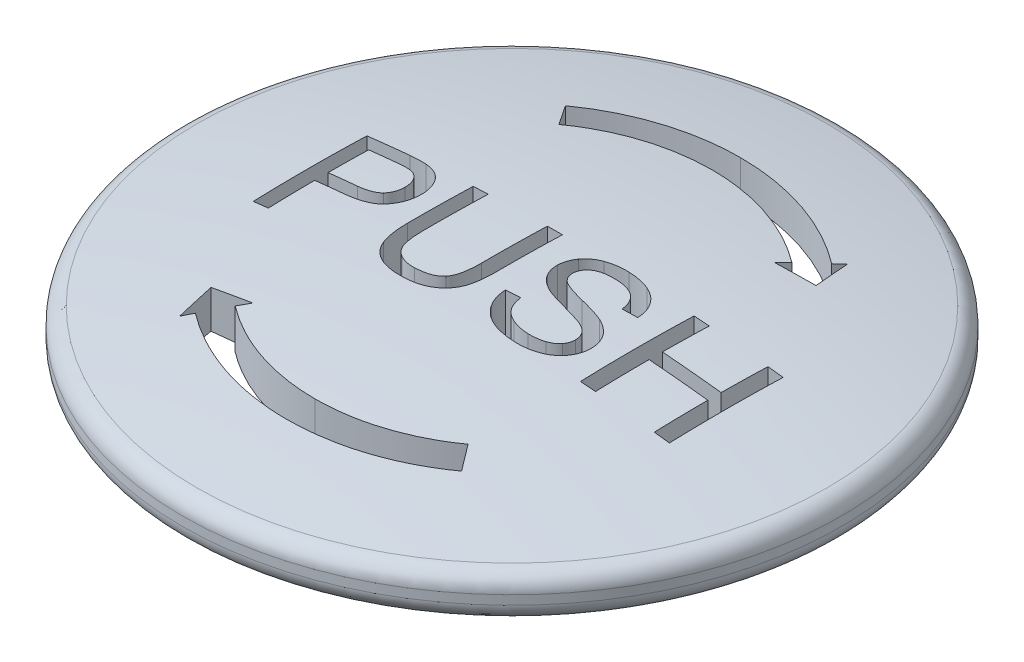
SolidWorks part; units mm, degrees
ref_plane "Front Plane" through (0, 0, 0) normal (0, 0, 1) x (1, 0, 0)
ref_plane "Top Plane" through (0, 0, 0) normal (0, 1, 0) x (1, 0, 0)
ref_plane "Right Plane" through (0, 0, 0) normal (1, 0, 0) x (0, 0, -1)
sketch "Sketch1" plane through (0, 0, 0) normal (0, 1, 0) x (1, 0, 0)
  circle A0 centre (0, 0) radius 20
  circle A1 centre (0, 0) radius 10
  dimension "D1" = 40
  dimension "D2" = 20
sketch "Sketch2" plane through (0, 0, 0) normal (0, 1, 0) x (1, 0, 0)
  circle A1 centre (0, 0) radius 10
  dimension "D1" = 20
extrude "Boss-Extrude2" add sketch "Sketch2" along normal blind 10 separate body
sketch "Sketch4" plane through (0, 0, 0) normal (0, 0, 1) x (1, 0, 0)
  line L0 (0, 10) -> (0, 15)
  line L1 (10, 10) -> (-10, 10) construction
  line L2 (0, 10) -> (21.3, 10)
  line L3 (22.5, 11.2) -> (22.5, 11.8205)
  line L4 (0, 15) -> (22.8044, 15) construction
  arc A0 (0, 15) -> (21.5211, 13) centre (0, -101.7897) cw
  arc A1 (22.5, 11.8205) -> (21.5211, 13) centre (21.3, 11.8205) ccw
  arc A2 (21.3, 10) -> (22.5, 11.2) centre (21.3, 11.2) ccw
  point P13 (22.5, 10)
  dimension "D3" = 1.2
  dimension "D1" = 5
  dimension "D2" = 22.5
  dimension "D4" = 3
revolve "Revolve1" add sketch "Sketch4" angle 360 about L0
sketch "Sketch9" plane through (0, 10, 0) normal (0, -1, 0) x (1, 0, 0)
  circle A0 centre (0, 0) radius 18
  dimension "D1" = 36
extrude "Cut-Extrude4" cut sketch "Sketch9" against normal blind 1.5
sketch "Sketch10" plane through (0, 11.5, 0) normal (0, -1, 0) x (1, 0, 0)
  circle A1 centre (0, 0) radius 18
  circle A2 centre (0, 0) radius 18
  dimension "D1" = 0
extrude "Cut-Extrude5" cut sketch "Sketch10" along normal blind 24.9
sketch "Sketch16" plane through (0, 0, 0) normal (0, 1, 0) x (1, 0, 0)
  line L0 (10.2566, 10.5007) -> (7.684, 10.2214)
  line L1 (7.684, 10.2214) -> (8.2069, 10.9019)
  line L2 (-7.9193, 11.1255) -> (-9.0492, 12.6983)
  line L3 (9.3805, 12.444) -> (9.8411, 13.0492)
  line L4 (9.8411, 13.0492) -> (10.2566, 10.5007)
  line L5 (-10.2699, -10.2796) -> (-7.6974, -10.0002)
  line L6 (-7.6974, -10.0002) -> (-8.2203, -10.6808)
  line L7 (7.9059, -10.9043) -> (9.0358, -12.4772)
  line L8 (-9.3939, -12.2228) -> (-9.8545, -12.828)
  line L9 (-9.8545, -12.828) -> (-10.2699, -10.2796)
  line L10 (-13.8958, -3.7717) -> (-13.8958, 3.9926)
  line L11 (-13.8958, 3.9926) -> (-10.9644, 3.9926)
  line L12 (-10.874, -0.6053) -> (-12.8657, -0.6053)
  line L13 (-12.8657, -0.6053) -> (-12.8657, -3.7717)
  line L14 (-12.8657, -3.7717) -> (-13.8958, -3.7717)
  line L15 (-12.8657, 0.3057) -> (-10.8596, 0.3057)
  line L16 (-10.8794, 3.0817) -> (-12.8657, 3.0817)
  line L17 (-12.8657, 3.0817) -> (-12.8657, 0.3057)
  line L18 (-1.5772, 3.9926) -> (-0.547, 3.9926)
  line L19 (-0.547, 3.9926) -> (-0.547, -0.4913)
  line L20 (-6.6413, -0.4913) -> (-6.6413, 3.9926)
  line L21 (-6.6413, 3.9926) -> (-5.6112, 3.9926)
  line L22 (-5.6112, 3.9926) -> (-5.6112, -0.4895)
  line L23 (-1.5772, -0.4895) -> (-1.5772, 3.9926)
  line L24 (0.8319, -1.2776) -> (1.7971, -1.1908)
  line L25 (6.7745, 1.802) -> (5.7877, 1.7263)
  line L26 (8.4445, -3.7717) -> (8.4445, 3.9926)
  line L27 (8.4445, 3.9926) -> (9.4746, 3.9926)
  line L28 (9.4746, 3.9926) -> (9.4746, 0.7937)
  line L29 (9.4746, 0.7937) -> (13.4868, 0.7937)
  line L30 (13.4868, 0.7937) -> (13.4868, 3.9926)
  line L31 (13.4868, 3.9926) -> (14.517, 3.9926)
  line L32 (14.517, 3.9926) -> (14.517, -3.7717)
  line L33 (14.517, -3.7717) -> (13.4868, -3.7717)
  line L34 (13.4868, -3.7717) -> (13.4868, -0.1173)
  line L35 (13.4868, -0.1173) -> (9.4746, -0.1173)
  line L36 (9.4746, -0.1173) -> (9.4746, -3.7717)
  line L37 (9.4746, -3.7717) -> (8.4445, -3.7717)
  circle A0 centre (0, 0) radius 15.6 construction
  spline S0 degree 3 poles (8.2069, 10.9019) (5.8458, 12.6991) (2.9604, 13.6721) (-0.0067, 13.6721) knots 0.2 0.2 0.2 0.2 0.3 0.3 0.3 0.3
  spline S1 degree 3 poles (-0.0067, 13.6721) (-2.8456, 13.6721) (-5.6137, 12.782) (-7.9193, 11.1255) knots 0.3 0.3 0.3 0.3 0.4 0.4 0.4 0.4
  spline S2 degree 3 poles (-9.0492, 12.6983) (-6.4141, 14.5912) (-3.2512, 15.6095) (-0.0067, 15.6095) knots 0.5 0.5 0.5 0.5 0.6 0.6 0.6 0.6
  spline S3 degree 3 poles (-0.0067, 15.6095) (3.3843, 15.6095) (6.6821, 14.4976) (9.3805, 12.444) knots 0.6 0.6 0.6 0.6 0.7 0.7 0.7 0.7
  spline S4 degree 3 poles (-8.2203, -10.6808) (-5.8592, -12.4779) (-2.9738, -13.451) (-0.0067, -13.451) knots 0.2 0.2 0.2 0.2 0.3 0.3 0.3 0.3
  spline S5 degree 3 poles (-0.0067, -13.451) (2.8323, -13.451) (5.6003, -12.5609) (7.9059, -10.9043) knots 0.3 0.3 0.3 0.3 0.4 0.4 0.4 0.4
  spline S6 degree 3 poles (9.0358, -12.4772) (6.4008, -14.3701) (3.2378, -15.3883) (-0.0067, -15.3883) knots 0.5 0.5 0.5 0.5 0.6 0.6 0.6 0.6
  spline S7 degree 3 poles (-0.0067, -15.3883) (-3.3977, -15.3883) (-6.6955, -14.2765) (-9.3939, -12.2228) knots 0.6 0.6 0.6 0.6 0.7 0.7 0.7 0.7
  spline S8 degree 3 poles (-10.9644, 3.9926) (-10.4494, 3.9926) (-10.0554, 3.9673) (-9.7825, 3.9185) knots 0.166667 0.166667 0.166667 0.166667 0.25 0.25 0.25 0.25
  spline S9 degree 3 poles (-9.7825, 3.9185) (-9.4011, 3.8553) (-9.0812, 3.7342) (-8.8227, 3.557) knots 0.25 0.25 0.25 0.25 0.333333 0.333333 0.333333 0.333333
  spline S10 degree 3 poles (-8.8227, 3.557) (-8.5642, 3.3781) (-8.3565, 3.1286) (-8.1992, 2.8088) knots 0.333333 0.333333 0.333333 0.333333 0.416667 0.416667 0.416667 0.416667
  spline S11 degree 3 poles (-8.1992, 2.8088) (-8.0419, 2.4889) (-7.9643, 2.1365) (-7.9643, 1.7515) knots 0.416667 0.416667 0.416667 0.416667 0.5 0.5 0.5 0.5
  spline S12 degree 3 poles (-7.9643, 1.7515) (-7.9643, 1.0936) (-8.1738, 0.5352) (-8.595, 0.0798) knots 0.5 0.5 0.5 0.5 0.583333 0.583333 0.583333 0.583333
  spline S13 degree 3 poles (-8.595, 0.0798) (-9.0142, -0.3776) (-9.7751, -0.6053) (-10.874, -0.6053) knots 0.583333 0.583333 0.583333 0.583333 0.666667 0.666667 0.666667 0.666667
  spline S14 degree 3 poles (-10.8596, 0.3057) (-10.1945, 0.3057) (-9.7245, 0.4286) (-9.4444, 0.6761) knots 0.111111 0.111111 0.111111 0.111111 0.222222 0.222222 0.222222 0.222222
  spline S15 degree 3 poles (-9.4444, 0.6761) (-9.1662, 0.9238) (-9.027, 1.2707) (-9.027, 1.7209) knots 0.222222 0.222222 0.222222 0.222222 0.333333 0.333333 0.333333 0.333333
  spline S16 degree 3 poles (-9.027, 1.7209) (-9.027, 2.0443) (-9.1082, 2.3226) (-9.2727, 2.5539) knots 0.333333 0.333333 0.333333 0.333333 0.444444 0.444444 0.444444 0.444444
  spline S17 degree 3 poles (-9.2727, 2.5539) (-9.4372, 2.7854) (-9.6541, 2.9389) (-9.9216, 3.0131) knots 0.444444 0.444444 0.444444 0.444444 0.555556 0.555556 0.555556 0.555556
  spline S18 degree 3 poles (-9.9216, 3.0131) (-10.0951, 3.0583) (-10.415, 3.0817) (-10.8794, 3.0817) knots 0.555556 0.555556 0.555556 0.555556 0.666667 0.666667 0.666667 0.666667
  spline S19 degree 3 poles (-0.547, -0.4913) (-0.547, -1.2722) (-0.6356, -1.8921) (-0.8109, -2.3511) knots 0.111111 0.111111 0.111111 0.111111 0.166667 0.166667 0.166667 0.166667
  spline S20 degree 3 poles (-0.8109, -2.3511) (-0.988, -2.8083) (-1.3061, -3.1825) (-1.7651, -3.4698) knots 0.166667 0.166667 0.166667 0.166667 0.222222 0.222222 0.222222 0.222222
  spline S21 degree 3 poles (-1.7651, -3.4698) (-2.2259, -3.7573) (-2.8278, -3.9018) (-3.5761, -3.9018) knots 0.222222 0.222222 0.222222 0.222222 0.277778 0.277778 0.277778 0.277778
  spline S22 degree 3 poles (-3.5761, -3.9018) (-4.3008, -3.9018) (-4.8953, -3.7771) (-5.3563, -3.5258) knots 0.277778 0.277778 0.277778 0.277778 0.333333 0.333333 0.333333 0.333333
  spline S23 degree 3 poles (-5.3563, -3.5258) (-5.8189, -3.2747) (-6.1479, -2.9132) (-6.3448, -2.4379) knots 0.333333 0.333333 0.333333 0.333333 0.388889 0.388889 0.388889 0.388889
  spline S24 degree 3 poles (-6.3448, -2.4379) (-6.5418, -1.9625) (-6.6413, -1.3138) (-6.6413, -0.4913) knots 0.388889 0.388889 0.388889 0.388889 0.444444 0.444444 0.444444 0.444444
  spline S25 degree 3 poles (-5.6112, -0.4895) (-5.6112, -1.1636) (-5.5478, -1.6626) (-5.4231, -1.9807) knots 0.611111 0.611111 0.611111 0.611111 0.666667 0.666667 0.666667 0.666667
  spline S26 degree 3 poles (-5.4231, -1.9807) (-5.2985, -2.3005) (-5.0852, -2.548) (-4.7797, -2.7197) knots 0.666667 0.666667 0.666667 0.666667 0.722222 0.722222 0.722222 0.722222
  spline S27 degree 3 poles (-4.7797, -2.7197) (-4.4761, -2.8933) (-4.1038, -2.98) (-3.6646, -2.98) knots 0.722222 0.722222 0.722222 0.722222 0.777778 0.777778 0.777778 0.777778
  spline S28 degree 3 poles (-3.6646, -2.98) (-2.9128, -2.98) (-2.376, -2.8083) (-2.0562, -2.4668) knots 0.777778 0.777778 0.777778 0.777778 0.833333 0.833333 0.833333 0.833333
  spline S29 degree 3 poles (-2.0562, -2.4668) (-1.7361, -2.1234) (-1.5772, -1.4655) (-1.5772, -0.4895) knots 0.833333 0.833333 0.833333 0.833333 0.888889 0.888889 0.888889 0.888889
  spline S30 degree 3 poles (1.7971, -1.1908) (1.8423, -1.5812) (1.9488, -1.9011) (2.117, -2.1524) knots 0.027778 0.027778 0.027778 0.027778 0.055556 0.055556 0.055556 0.055556
  spline S31 degree 3 poles (2.117, -2.1524) (2.2851, -2.4017) (2.5454, -2.6042) (2.8978, -2.7595) knots 0.055556 0.055556 0.055556 0.055556 0.083333 0.083333 0.083333 0.083333
  spline S32 degree 3 poles (2.8978, -2.7595) (3.2502, -2.9132) (3.6479, -2.9908) (4.0889, -2.9908) knots 0.083333 0.083333 0.083333 0.083333 0.111111 0.111111 0.111111 0.111111
  spline S33 degree 3 poles (4.0889, -2.9908) (4.4809, -2.9908) (4.8261, -2.933) (5.1262, -2.8155) knots 0.111111 0.111111 0.111111 0.111111 0.138889 0.138889 0.138889 0.138889
  spline S34 degree 3 poles (5.1262, -2.8155) (5.4263, -2.6981) (5.6486, -2.5372) (5.7949, -2.3331) knots 0.138889 0.138889 0.138889 0.138889 0.166667 0.166667 0.166667 0.166667
  spline S35 degree 3 poles (5.7949, -2.3331) (5.9412, -2.1288) (6.0154, -1.9065) (6.0154, -1.668) knots 0.166667 0.166667 0.166667 0.166667 0.194444 0.194444 0.194444 0.194444
  spline S36 degree 3 poles (6.0154, -1.668) (6.0154, -1.4257) (5.9448, -1.2142) (5.8039, -1.0317) knots 0.194444 0.194444 0.194444 0.194444 0.222222 0.222222 0.222222 0.222222
  spline S37 degree 3 poles (5.8039, -1.0317) (5.663, -0.851) (5.4299, -0.6992) (5.1044, -0.5745) knots 0.222222 0.222222 0.222222 0.222222 0.25 0.25 0.25 0.25
  spline S38 degree 3 poles (5.1044, -0.5745) (4.8967, -0.4949) (4.4357, -0.3684) (3.7218, -0.1969) knots 0.25 0.25 0.25 0.25 0.277778 0.277778 0.277778 0.277778
  spline S39 degree 3 poles (3.7218, -0.1969) (3.008, -0.0251) (2.5092, 0.1358) (2.2237, 0.2875) knots 0.277778 0.277778 0.277778 0.277778 0.305556 0.305556 0.305556 0.305556
  spline S40 degree 3 poles (2.2237, 0.2875) (1.8531, 0.4828) (1.5784, 0.7249) (1.3977, 1.0124) knots 0.305556 0.305556 0.305556 0.305556 0.333333 0.333333 0.333333 0.333333
  spline S41 degree 3 poles (1.3977, 1.0124) (1.2152, 1.2997) (1.1248, 1.6231) (1.1248, 1.9792) knots 0.333333 0.333333 0.333333 0.333333 0.361111 0.361111 0.361111 0.361111
  spline S42 degree 3 poles (1.1248, 1.9792) (1.1248, 2.3732) (1.2368, 2.7402) (1.4591, 3.0799) knots 0.361111 0.361111 0.361111 0.361111 0.388889 0.388889 0.388889 0.388889
  spline S43 degree 3 poles (1.4591, 3.0799) (1.6814, 3.4215) (2.005, 3.68) (2.4332, 3.8571) knots 0.388889 0.388889 0.388889 0.388889 0.416667 0.416667 0.416667 0.416667
  spline S44 degree 3 poles (2.4332, 3.8571) (2.8598, 4.0342) (3.3352, 4.1228) (3.8574, 4.1228) knots 0.416667 0.416667 0.416667 0.416667 0.444444 0.444444 0.444444 0.444444
  spline S45 degree 3 poles (3.8574, 4.1228) (4.4321, 4.1228) (4.9401, 4.0306) (5.3793, 3.8443) knots 0.444444 0.444444 0.444444 0.444444 0.472222 0.472222 0.472222 0.472222
  spline S46 degree 3 poles (5.3793, 3.8443) (5.8183, 3.66) (6.1563, 3.3871) (6.393, 3.0257) knots 0.472222 0.472222 0.472222 0.472222 0.5 0.5 0.5 0.5
  spline S47 degree 3 poles (6.393, 3.0257) (6.6299, 2.666) (6.7565, 2.2576) (6.7745, 1.802) knots 0.5 0.5 0.5 0.5 0.527778 0.527778 0.527778 0.527778
  spline S48 degree 3 poles (5.7877, 1.7263) (5.7353, 2.216) (5.5564, 2.5865) (5.2509, 2.836) knots 0.555556 0.555556 0.555556 0.555556 0.583333 0.583333 0.583333 0.583333
  spline S49 degree 3 poles (5.2509, 2.836) (4.9455, 3.0871) (4.4937, 3.2118) (3.8972, 3.2118) knots 0.583333 0.583333 0.583333 0.583333 0.611111 0.611111 0.611111 0.611111
  spline S50 degree 3 poles (3.8972, 3.2118) (3.2754, 3.2118) (2.8218, 3.098) (2.5382, 2.8702) knots 0.611111 0.611111 0.611111 0.611111 0.638889 0.638889 0.638889 0.638889
  spline S51 degree 3 poles (2.5382, 2.8702) (2.2543, 2.6425) (2.1116, 2.3678) (2.1116, 2.0461) knots 0.638889 0.638889 0.638889 0.638889 0.666667 0.666667 0.666667 0.666667
  spline S52 degree 3 poles (2.1116, 2.0461) (2.1116, 1.7678) (2.2127, 1.5382) (2.4134, 1.3574) knots 0.666667 0.666667 0.666667 0.666667 0.694444 0.694444 0.694444 0.694444
  spline S53 degree 3 poles (2.4134, 1.3574) (2.6121, 1.1785) (3.1273, 0.9924) (3.9623, 0.8045) knots 0.694444 0.694444 0.694444 0.694444 0.722222 0.722222 0.722222 0.722222
  spline S54 degree 3 poles (3.9623, 0.8045) (4.7972, 0.6148) (5.3701, 0.4502) (5.681, 0.3093) knots 0.722222 0.722222 0.722222 0.722222 0.75 0.75 0.75 0.75
  spline S55 degree 3 poles (5.681, 0.3093) (6.131, 0.1014) (6.4654, -0.1607) (6.6805, -0.4805) knots 0.75 0.75 0.75 0.75 0.777778 0.777778 0.777778 0.777778
  spline S56 degree 3 poles (6.6805, -0.4805) (6.8956, -0.7986) (7.0022, -1.1654) (7.0022, -1.5812) knots 0.777778 0.777778 0.777778 0.777778 0.805556 0.805556 0.805556 0.805556
  spline S57 degree 3 poles (7.0022, -1.5812) (7.0022, -1.9951) (6.8846, -2.3819) (6.6479, -2.7469) knots 0.805556 0.805556 0.805556 0.805556 0.833333 0.833333 0.833333 0.833333
  spline S58 degree 3 poles (6.6479, -2.7469) (6.4112, -3.112) (6.0732, -3.3958) (5.6304, -3.5981) knots 0.833333 0.833333 0.833333 0.833333 0.861111 0.861111 0.861111 0.861111
  spline S59 degree 3 poles (5.6304, -3.5981) (5.1876, -3.8006) (4.6906, -3.9018) (4.1358, -3.9018) knots 0.861111 0.861111 0.861111 0.861111 0.888889 0.888889 0.888889 0.888889
  spline S60 degree 3 poles (4.1358, -3.9018) (3.4346, -3.9018) (2.8472, -3.7988) (2.3736, -3.5945) knots 0.888889 0.888889 0.888889 0.888889 0.916667 0.916667 0.916667 0.916667
  spline S61 degree 3 poles (2.3736, -3.5945) (1.8983, -3.3902) (1.5278, -3.0832) (1.2585, -2.671) knots 0.916667 0.916667 0.916667 0.916667 0.944444 0.944444 0.944444 0.944444
  spline S62 degree 3 poles (1.2585, -2.671) (0.9875, -2.2607) (0.8465, -1.7963) (0.8319, -1.2776) knots 0.944444 0.944444 0.944444 0.944444 1 1 1 1
  dimension "D1" = 31.2
extrude "Cut-Extrude9" cut sketch "Sketch16" along normal blind 24.9
